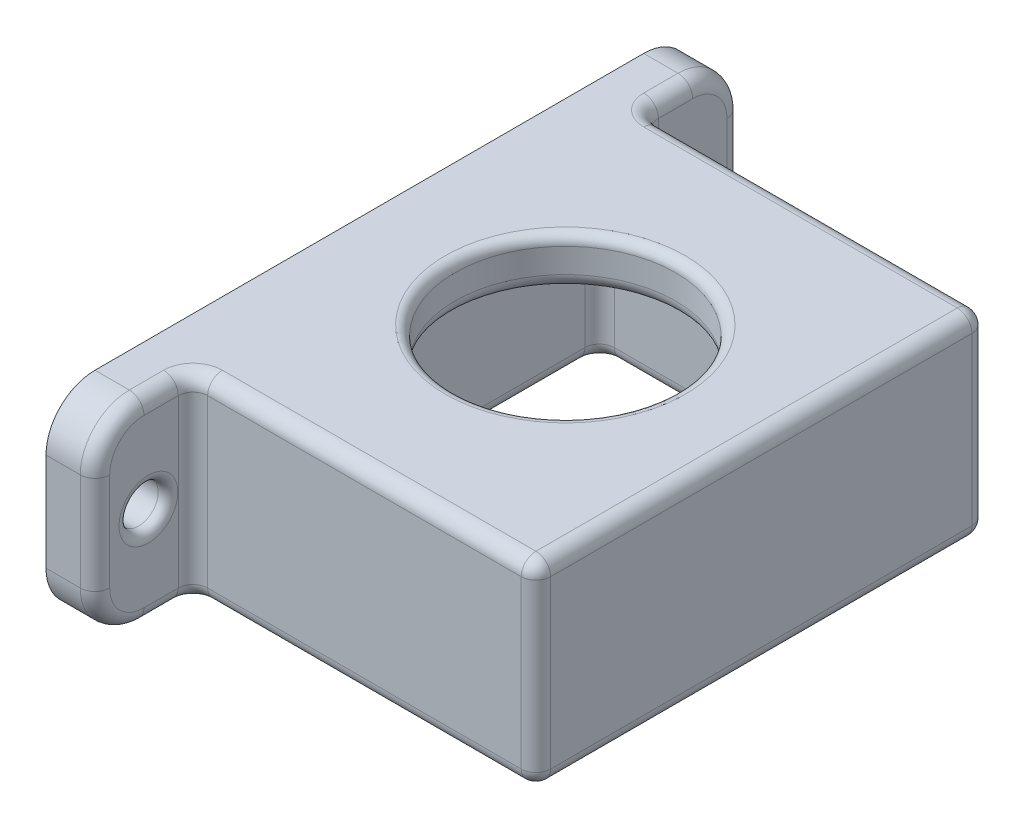
SolidWorks part; units mm, degrees
ref_plane "Front Plane" through (0, 0, 0) normal (0, 0, 1) x (1, 0, 0)
ref_plane "Top Plane" through (0, 0, 0) normal (0, 1, 0) x (1, 0, 0)
ref_plane "Right Plane" through (0, 0, 0) normal (1, 0, 0) x (0, 0, -1)
sketch "Sketch2" plane through (0, 0, 0) normal (0, 1, 0) x (1, 0, 0)
  line L1 (-15.5, -19) -> (15.5, -19)
  line L2 (-15.5, -19) -> (-15.5, 19)
  line L3 (-15.5, 19) -> (15.5, 19)
  line L4 (15.5, -19) -> (15.5, 19)
  line L5 (0, 19) -> (0, -19) construction
  line L6 (-15.5, 0) -> (15.5, 0) construction
  line L7 (-20, -23) -> (20, -23)
  line L8 (-20, -23) -> (-20, 23)
  line L9 (-20, 23) -> (20, 23)
  line L10 (20, -23) -> (20, 23)
  line L11 (0, 23) -> (0, -23) construction
  line L12 (-20, 0) -> (20, 0) construction
  point P0 (0, 0)
  point P4 (0, 0)
  dimension "D1" = 31
  dimension "D2" = 38
  dimension "D3" = 40
  dimension "D4" = 46
extrude "Boss-Extrude1" add sketch "Sketch2" along normal blind 15
sketch "Sketch4" plane through (0, 15, 0) normal (0, 1, 0) x (1, 0, 0)
  line L1 (-20, -23) -> (20, -23)
  line L2 (-20, -23) -> (-20, 23)
  line L3 (-20, 23) -> (20, 23)
  line L4 (20, -23) -> (20, 23)
  line L5 (0, 23) -> (0, -23) construction
  line L6 (-20, 0) -> (20, 0) construction
  point P0 (0, 0)
extrude "Boss-Extrude2" add sketch "Sketch4" along normal blind 5
sketch "Sketch5" plane through (0, 20, 0) normal (0, 1, 0) x (1, 0, 0)
  circle A0 centre (0, 0) radius 11.25
  dimension "D1" = 22.5
extrude "Cut-Extrude1" cut sketch "Sketch5" against normal blind 5
sketch "Sketch8" plane through (0, 0, 23) normal (0, 0, 1) x (1, 0, 0)
  line L0 (-20, 0) -> (20, 0) construction
  line L1 (-20, 20) -> (-15, 20)
  line L2 (-20, 20) -> (-20, 0)
  line L3 (-20, 0) -> (-15, 0)
  line L4 (-15, 20) -> (-15, 0)
  dimension "D1" = 5
extrude "Boss-Extrude3" add sketch "Sketch8" along normal blind 10
mirror "Mirror1" about plane through (0, 0, 0) normal (0, 0, 1) of "Boss-Extrude3"
fillet "Fillet2" radius 5 4 edges at (-17.5, 0, -33) (-17.5, 20, -33) (-17.5, 0, 33) (-17.5, 20, 33)
sketch "Sketch9" plane through (0, 0, 0) normal (1, 0, 0) x (0, 0, -1)
  line L0 (-33, 10) -> (-23, 10) construction
  line L1 (-33, 5) -> (-33, 15) construction
  line L2 (-23, 0) -> (-23, 20) construction
  line L3 (0, 55) -> (0, -55) construction
  circle A0 centre (-27.5509, 10) radius 2
  circle A1 centre (27.5509, 10) radius 2
extrude "Cut-Extrude2" cut sketch "Sketch9" against normal blind 26
fillet "Fillet3" radius 1.5 33 edges at (-15, 10, -33) (-15, 10, 33) (-15, 18.5355, -31.5355) (-15, 1.4645, -31.5355) (-15, 18.5355, 31.5355) (-15, 1.4645, 31.5355) (-15, 20, -25.5) (-15, 0, -25.5) (-15, 20, 25.5) (-15, 0, 25.5) (2.5, 0, -23) (2.5, 20, -23) (-15, 10, -23) (2.5, 0, 23) (2.5, 20, 23) (-15, 10, 23) (20, 10, 23) (20, 0, 0) (20, 20, 0) (20, 10, -23) (-15.5, 0, 0) (-15.5, 15, 0) (-15.5, 7.5, -19) (0, 0, -19) (0, 15, -19) (15.5, 7.5, -19) (15.5, 0, 0) (15.5, 15, 0) (15.5, 7.5, 19) (-15.5, 7.5, 19) (0, 0, 19) (0, 15, 19) (0, 15, 11.25)
fillet "Fillet4" radius 1 5 edges at (-20, 10, -29.5509) (-15, 12, -27.5509) (-20, 10, 25.5509) (-15, 8, 27.5509) (0, 20, 11.25)
